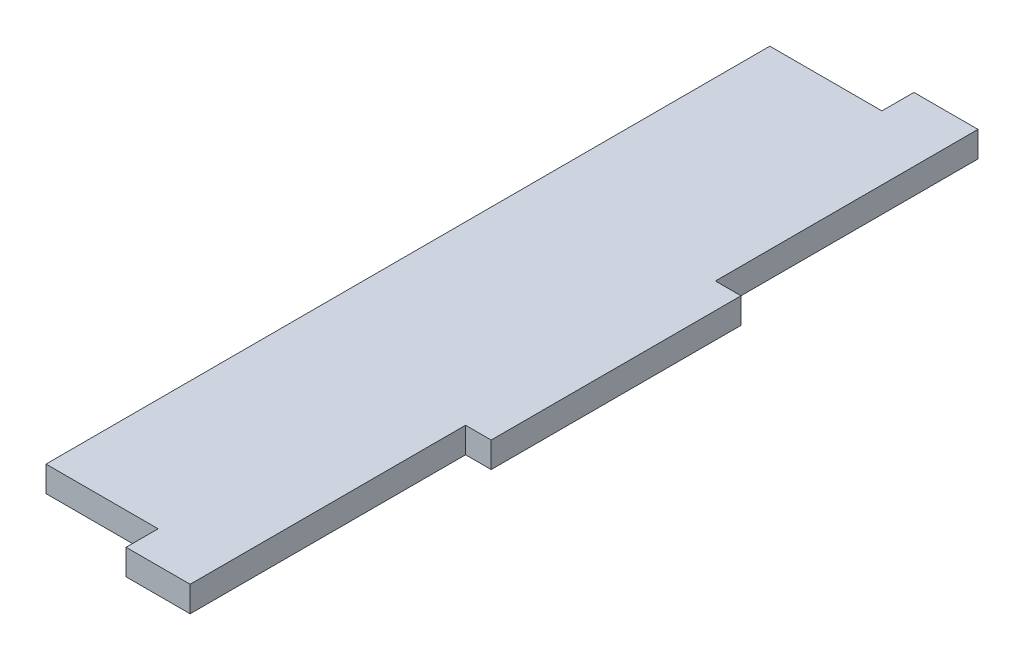
SolidWorks part; units mm, degrees
ref_plane "Front Plane" through (0, 0, 0) normal (0, 0, 1) x (1, 0, 0)
ref_plane "Top Plane" through (0, 0, 0) normal (0, 1, 0) x (1, 0, 0)
ref_plane "Right Plane" through (0, 0, 0) normal (1, 0, 0) x (0, 0, -1)
sketch "Sketch1" plane through (0, 0, 0) normal (0, 1, 0) x (1, 0, 0)
  line L0 (17.5, 113) -> (17.5, 114)
  line L1 (0, 0) -> (17.5, 0)
  line L2 (0, 0) -> (0, 113)
  line L3 (0, 113) -> (17.5, 113)
  line L5 (17.5, -1) -> (27.5, -1)
  line L6 (17.5, -1) -> (17.5, 0)
  line L7 (17.5, 114) -> (27.5, 114)
  line L8 (27.5, -1) -> (27.5, 114)
  dimension "D1" = 1
  dimension "D2" = 1
  dimension "D3" = 113
  dimension "D4" = 17.5
  dimension "D5" = 10
extrude "Boss-Extrude1" add sketch "Sketch1" along normal blind 4
sketch "Sketch2" plane through (0, 4, 0) normal (0, 1, 0) x (1, 0, 0)
  line L0 (17.5, 0) -> (17.5, -1) construction
  line L1 (27.5, -1) -> (17.5, -1)
  line L2 (27.5, -1) -> (27.5, -5)
  line L3 (27.5, -5) -> (17.5, -5)
  line L4 (17.5, -1) -> (17.5, -5)
  line L6 (27.5, 114) -> (17.5, 114)
  line L7 (27.5, 114) -> (27.5, 118)
  line L8 (27.5, 118) -> (17.5, 118)
  line L9 (17.5, 114) -> (17.5, 118)
  dimension "D1" = 4
  dimension "D2" = 4
  dimension "D3" = 10
extrude "Boss-Extrude2" add sketch "Sketch2" against normal blind 4
sketch "Sketch3" plane through (0, 4, 0) normal (0, 1, 0) x (1, 0, 0)
  line L0 (27.5, -5) -> (27.5, 118) construction
  line L1 (27.5, 77) -> (31.5, 77)
  line L2 (27.5, 77) -> (27.5, 38)
  line L3 (27.5, 38) -> (31.5, 38)
  line L4 (31.5, 77) -> (31.5, 38)
  line L5 (27.5, 118) -> (17.5, 118) construction
  dimension "D1" = 4
  dimension "D2" = 39
  dimension "D3" = 41
extrude "Boss-Extrude3" add sketch "Sketch3" against normal blind 4
